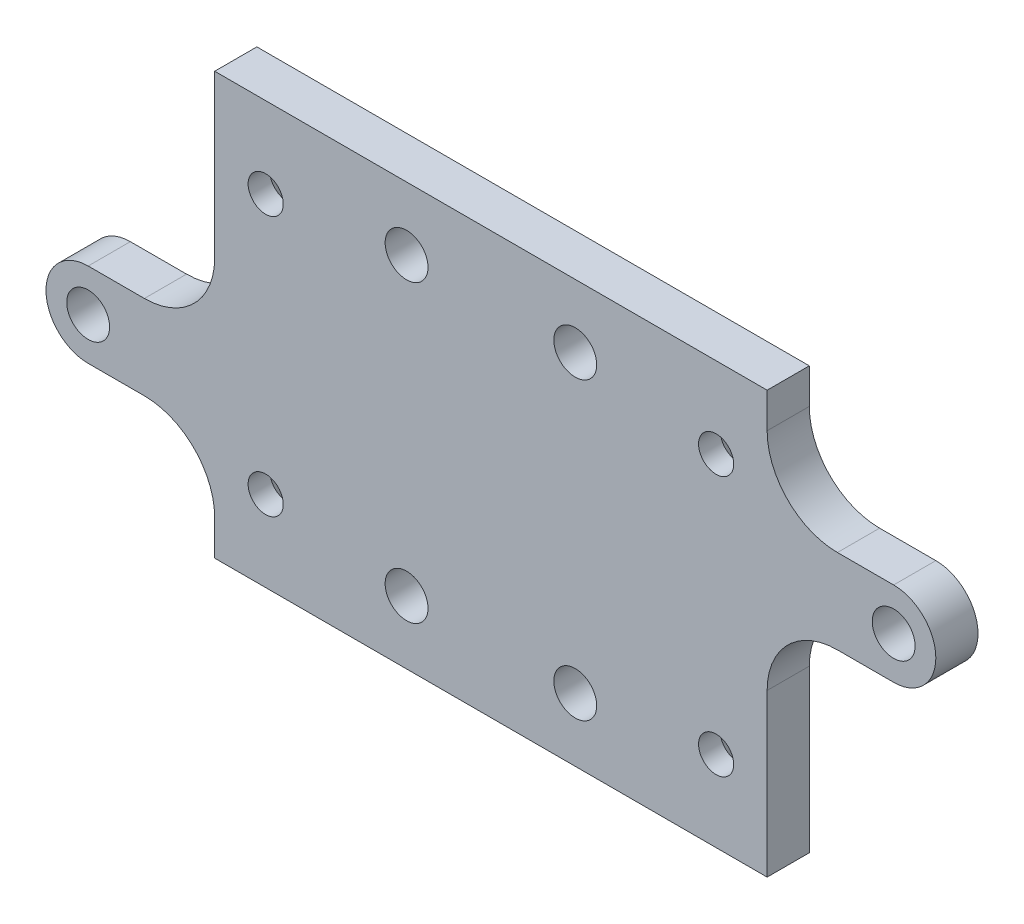
SolidWorks part; units mm, degrees
material "Thornel Mat VMA"
ref_plane "前视基准面" through (0, 0, 0) normal (0, 0, 1) x (1, 0, 0)
ref_plane "上视基准面" through (0, 0, 0) normal (0, 1, 0) x (1, 0, 0)
ref_plane "右视基准面" through (0, 0, 0) normal (1, 0, 0) x (0, 0, -1)
sketch "草图1" plane through (0, 0, 0) normal (0, 0, 1) x (1, 0, 0)
  line L1 (-19.65, -15) -> (19.65, -15)
  line L2 (-19.65, -15) -> (-19.65, 15)
  line L3 (-19.65, 15) -> (19.65, 15)
  line L4 (19.65, -15) -> (19.65, 15)
  line L5 (-19.65, -15) -> (19.65, 15) construction
  line L6 (-19.65, 15) -> (19.65, -15) construction
  point P0 (0, 0)
  dimension "D1" = 30
  dimension "D2" = 39.3
extrude "凸台-拉伸1" add sketch "草图1" along normal blind 3
sketch "草图2" plane through (0, 0, 3) normal (0, 0, 1) x (1, 0, 0)
  line L0 (-28.65, -7.5) -> (-19.65, -7.5)
  line L1 (-19.65, 15) -> (-19.65, -15) construction
  line L2 (-19.65, -7.5) -> (-19.65, -1.5)
  line L3 (-19.65, -1.5) -> (-28.65, -1.5)
  line L4 (-19.65, -15) -> (19.65, -15) construction
  arc A0 (-28.65, -1.5) -> (-28.65, -7.5) centre (-28.65, -4.5) ccw
  circle A1 centre (-28.65, -4.5) radius 1.525
  dimension "D1" = 6
  dimension "D2" = 3.05
  dimension "D3" = 10.5
  dimension "D4" = 9
extrude "凸台-拉伸2" add sketch "草图2" against normal up to surface (3 mm away) up to face at (0, 0, 0)
sketch "草图4" plane through (0, 0, 3) normal (0, 0, 1) x (1, 0, 0)
  line L0 (28.65, 7.5) -> (19.65, 7.5)
  line L1 (19.65, -15) -> (19.65, 15) construction
  line L2 (19.65, 7.5) -> (19.65, 1.5)
  line L3 (19.65, 1.5) -> (28.65, 1.5)
  line L4 (19.65, 15) -> (-19.65, 15) construction
  circle A0 centre (28.65, 4.5) radius 1.525
  arc A1 (28.65, 1.5) -> (28.65, 7.5) centre (28.65, 4.5) ccw
  dimension "D1" = 6
  dimension "D2" = 3.05
  dimension "D3" = 10.5
  dimension "D4" = 9
extrude "凸台-拉伸3" add sketch "草图4" against normal up to surface (3 mm away) up to face at (-12.45, -2.25, 0)
fillet "圆角1" radius 5 4 edges at (-19.65, -7.5, 1.5) (-19.65, -1.5, 1.5) (19.65, 7.5, 1.5) (19.65, 1.5, 1.5)
sketch "草图5" plane through (0, 0, 3) normal (0, 0, 1) x (1, 0, 0)
  line L1 (-6, -10.5) -> (6, -10.5) construction
  line L2 (-6, -10.5) -> (-6, 10.5) construction
  line L3 (-6, 10.5) -> (6, 10.5) construction
  line L4 (6, -10.5) -> (6, 10.5) construction
  line L5 (-6, -10.5) -> (6, 10.5) construction
  line L6 (-6, 10.5) -> (6, -10.5) construction
  circle A0 centre (6, 10.5) radius 1.525
  circle A1 centre (-6, 10.5) radius 1.525
  circle A2 centre (-6, -10.5) radius 1.525
  circle A3 centre (6, -10.5) radius 1.525
  point P0 (0, 0)
  dimension "D3" = 3.05
  dimension "D1" = 12
  dimension "D2" = 21
extrude "切除-拉伸1" cut sketch "草图5" against normal blind 30
sketch "草图6" plane through (0, 0, 0) normal (0, 0, -1) x (-1, 0, 0)
  line L1 (-16.0215, -9.25) -> (16.0215, -9.25) construction
  line L2 (-16.0215, -9.25) -> (-16.0215, 9.25) construction
  line L3 (-16.0215, 9.25) -> (16.0215, 9.25) construction
  line L4 (16.0215, -9.25) -> (16.0215, 9.25) construction
  line L5 (0, 9.25) -> (0, -9.25) construction
  line L6 (-16.0215, 0) -> (16.0215, 0) construction
  circle A4 centre (0, 18.5) radius 1.25 construction
  circle A5 centre (16.0215, 9.25) radius 1.25
  circle A6 centre (0, -18.5) radius 1.25 construction
  circle A7 centre (-16.0215, -9.25) radius 1.25
  circle A10 centre (16.0215, -9.25) radius 1.25
  circle A11 centre (-16.0215, 9.25) radius 1.25
  point P1 (0, 0)
  dimension "D3" = 2.5
  dimension "D1" = 18.5
  dimension "D2" = 32.0429
extrude "切除-拉伸2" cut sketch "草图6" against normal blind 40
hole_wizard "M2.5 十字槽半沉头木螺钉的锥形沉头孔1" positions "草图7" profile "草图8" countersink size "M2.5" standard "GB" end condition through all
sketch "草图7" plane through (0, 0, 0) normal (0, 0, -1) x (-1, 0, 0)
  point P0 (-16.0215, 9.25)
  point P3 (-16.0215, -9.25)
  point P6 (16.0215, 9.25)
  point P9 (16.0215, -9.25)
sketch "草图8" plane through (16.0215, 9.25, 0) normal (1, 0, 0) x (0, 1, 0)
  line L0 (0, 0) -> (0, 3)
  line L1 (0, 3) -> (1.25, 3)
  line L2 (1.25, 3) -> (1.25, 1.45)
  line L3 (1.25, 1.45) -> (2.7, 0)
  line L5 (2.7, 0) -> (0, 0)
  line L6 (-1.25, 1.45) -> (-2.7, 0) construction
  line L11 (0, -6.35) -> (0, 107.95) construction
  dimension "通孔孔直径" = 2.5
  dimension "通孔孔深度" = 3
  dimension "近端锥形沉头孔直径" = 5.4
  dimension "近端锥形沉头孔角度" = 90
